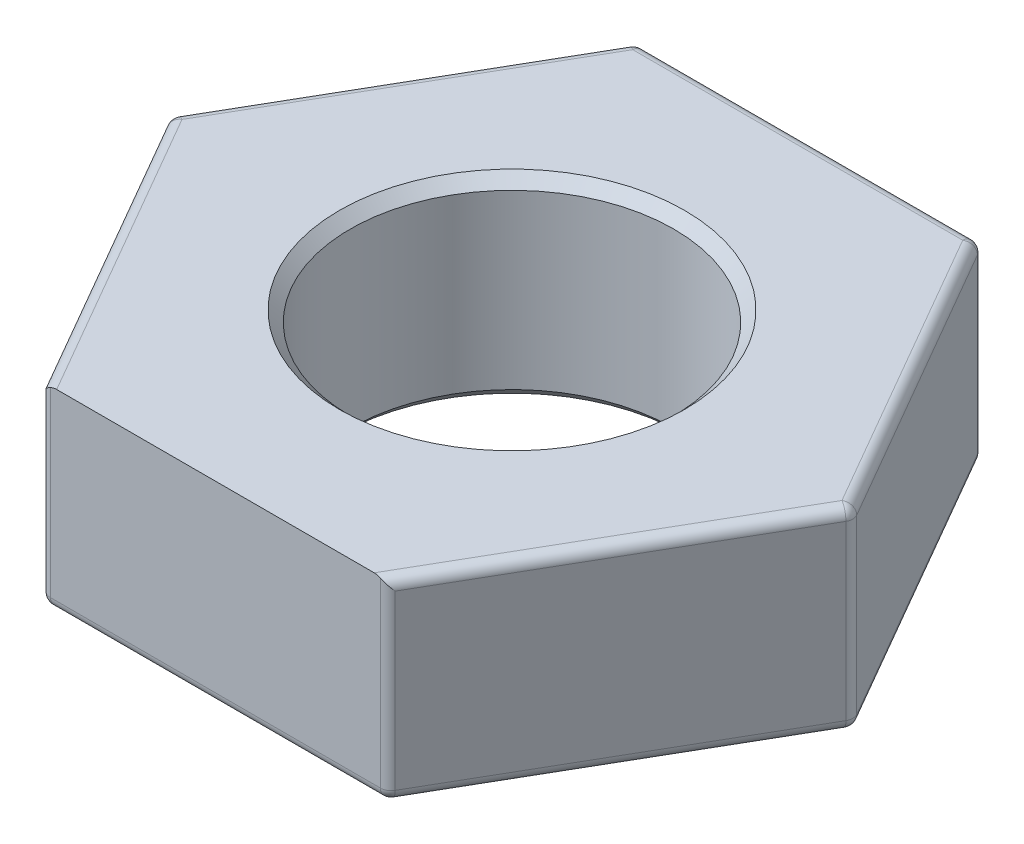
SolidWorks part; units mm, degrees
ref_plane "Front Plane" through (0, 0, 0) normal (0, 0, 1) x (1, 0, 0)
ref_plane "Top Plane" through (0, 0, 0) normal (0, 1, 0) x (1, 0, 0)
ref_plane "Right Plane" through (0, 0, 0) normal (1, 0, 0) x (0, 0, -1)
sketch "Sketch1" plane through (0, 0, 0) normal (0, 1, 0) x (1, 0, 0)
  line L2 (-1.5877, 2.75) -> (1.5877, 2.75)
  line L3 (-1.5877, -2.75) -> (-3.1754, 0)
  line L4 (-3.1754, 0) -> (-1.5877, 2.75)
  line L5 (1.5877, -2.75) -> (3.1754, 0)
  line L6 (3.1754, 0) -> (1.5877, 2.75)
  line L7 (-1.5877, -2.75) -> (1.5877, -2.75)
  circle A0 centre (0, 0) radius 1.5
  circle A1 centre (0, 0) radius 2.75
  dimension "D1" = 3
  dimension "D2" = 5.5
extrude "Boss-Extrude2" add sketch "Sketch1" along normal blind 1.8 contours A1 L2 L4 | A1 L4 L3 | A1 L6 L2 | A1 L5 L6 | A1 L3 L7 | A1 L7 L5 | A1 A0
fillet "Fillet1" radius 0.1 17 edges at (2.3816, 0, -1.375) (2.3816, 1.8, -1.375) (0, 0, -2.75) (0, 1.8, -2.75) (-2.3816, 0, -1.375) (-2.3816, 1.8, -1.375) (-2.3816, 0, 1.375) (-2.3816, 1.8, 1.375) (0, 0, 2.75) (2.3816, 0, 1.375) (2.3816, 1.8, 1.375) (1.5877, 0.9, 2.75) (-1.5877, 0.9, 2.75) (-3.1754, 0.9, 0) (-1.5877, 0.9, -2.75) (1.5877, 0.9, -2.75) (3.1754, 0.9, 0)
chamfer "Chamfer1" distance 0.1 angle 45 2 edges at (0, 1.8, 1.5) (0, 0, 1.5)
